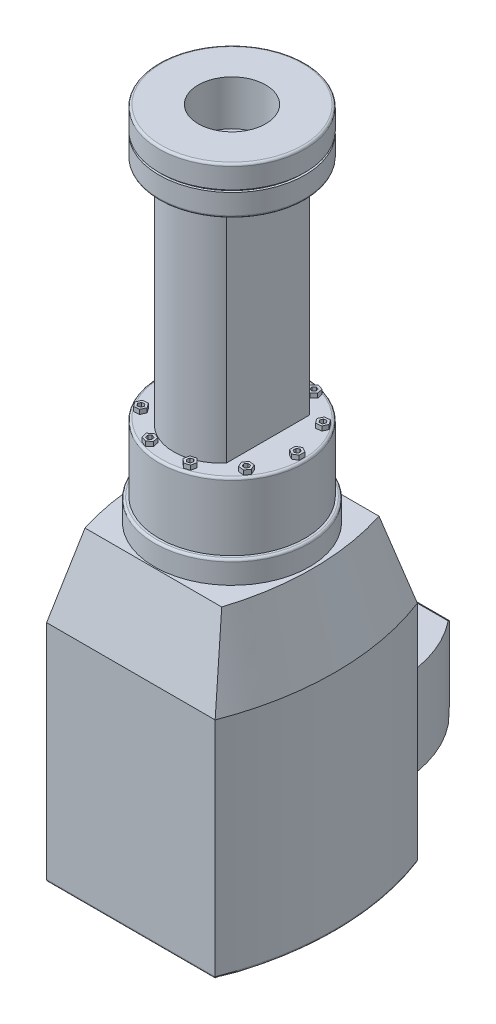
SolidWorks part; units mm, degrees
material "AISI 1020 Steel, Cold Rolled"
ref_plane "Front Plane" through (0, 0, 0) normal (0, 0, 1) x (1, 0, 0)
ref_plane "Top Plane" through (0, 0, 0) normal (0, 1, 0) x (1, 0, 0)
ref_plane "Right Plane" through (0, 0, 0) normal (1, 0, 0) x (0, 0, -1)
sketch "Sketch1" plane through (0, 0, 0) normal (0, 1, 0) x (1, 0, 0)
  line L0 (0, -45) -> (0, 45) construction
  line L1 (37.5, 45) -> (-37.5, 45)
  line L2 (37.5, -45) -> (-37.5, -45)
  arc A0 (-37.5, 45) -> (-37.5, -45) centre (79.119, 0) ccw
  arc A1 (37.5, 45) -> (37.5, -45) centre (-79.119, 0) cw
  point P4 (0, 0)
  point P7 (0, 45)
  point P11 (0, -45)
  dimension "D3" = 125
  dimension "D1" = 75
  dimension "D2" = 90
extrude "Boss-Extrude1" add sketch "Sketch1" along normal blind 100
sketch "Sketch2" plane through (0, 100, 0) normal (0, 1, 0) x (1, 0, 0)
  line L2 (-37.5, -45) -> (37.5, -45)
  line L3 (37.5, 45) -> (-37.5, 45)
  line L4 (-37.5, -45) -> (37.5, -45)
  line L5 (37.5, 45) -> (-37.5, 45)
  arc A2 (-37.5, 45) -> (-37.5, -45) centre (79.119, 0) ccw
  arc A3 (37.5, -45) -> (37.5, 45) centre (-79.119, 0) ccw
  arc A4 (-37.5, 45) -> (-37.5, -45) centre (79.119, 0) ccw
  arc A5 (37.5, -45) -> (37.5, 45) centre (-79.119, 0) ccw
  dimension "D1" = 0
ref_plane "Plane1" through (0, 135, 0) normal (0, 1, 0) x (1, 0, 0)
sketch "Sketch3" plane through (0, 135, 0) normal (0, 1, 0) x (1, 0, 0)
  line L5 (30.4255, 35) -> (-30.4255, 35)
  line L6 (-30.4255, -35) -> (30.4255, -35)
  line L7 (30.4255, 35) -> (-30.4255, 35)
  line L8 (-30.4255, -35) -> (30.4255, -35)
  arc A4 (-30.4255, 35) -> (-30.4255, -35) centre (79.119, 0) ccw
  arc A5 (30.4255, -35) -> (30.4255, 35) centre (-79.119, 0) ccw
  arc A6 (-30.4255, 35) -> (-30.4255, -35) centre (79.119, 0) ccw
  arc A7 (30.4255, -35) -> (30.4255, 35) centre (-79.119, 0) ccw
  dimension "D1" = 10
loft "Loft1" add profiles "Sketch2", "Sketch3"
sketch "Sketch4" plane through (0, 135, 0) normal (0, 1, 0) x (1, 0, 0)
  circle A0 centre (0, 0) radius 34.5
  dimension "D1" = 69
extrude "Boss-Extrude2" add sketch "Sketch4" along normal blind 10
sketch "Sketch5" plane through (0, 145, 0) normal (0, 1, 0) x (1, 0, 0)
  circle A2 centre (0, 0) radius 32.5
  circle A3 centre (0, 0) radius 32.5
  dimension "D1" = 2
extrude "Boss-Extrude3" add sketch "Sketch5" along normal blind 30
sketch "Sketch6" plane through (0, 175, 0) normal (0, 1, 0) x (1, 0, 0)
  line L0 (0, 0) -> (29, 0) construction
  line L1 (27.8349, -0.6726) -> (29, -1.3453)
  line L2 (29, 2.5) -> (26.8349, 1.25)
  line L3 (26.8349, 1.25) -> (26.8349, -1.25)
  line L4 (26.8349, -1.25) -> (29, -2.5)
  line L5 (29, -2.5) -> (31.1651, -1.25)
  line L6 (31.1651, -1.25) -> (31.1651, 1.25)
  line L7 (31.1651, 1.25) -> (29, 2.5)
  line L8 (29, -1.3453) -> (30.1651, -0.6726)
  line L9 (30.1651, -0.6726) -> (30.1651, 0.6726)
  line L10 (30.1651, 0.6726) -> (29, 1.3453)
  line L11 (29, 1.3453) -> (27.8349, 0.6726)
  line L12 (27.8349, 0.6726) -> (27.8349, -0.6726)
  circle A0 centre (29, 0) radius 2.1651 construction
  dimension "D1" = 29
  dimension "D2" = 5
  dimension "D3" = 1
extrude "Boss-Extrude4" add sketch "Sketch6" along normal blind 2
pattern_circular "CirPattern1" count 10 over 360 about axis through (0, 0, 0) along (0, 1, 0) of "Boss-Extrude4"
sketch "Sketch7" plane through (0, 175, 0) normal (0, 1, 0) x (1, 0, 0)
  line L0 (0, -14.804) -> (0, 14.804) construction
  line L1 (0, 0) -> (16, 0) construction
  line L2 (16, -18.5) -> (16, 18.5)
  line L3 (-16, -18.5) -> (-16, 18.5)
  arc A0 (-16, 18.5) -> (16, 18.5) centre (0, 4.8985) cw
  arc A1 (-16, -18.5) -> (16, -18.5) centre (0, -4.8985) ccw
  point P5 (0, 0)
  point P11 (16, 0)
  dimension "D3" = 21
  dimension "D1" = 16
  dimension "D2" = 37
extrude "Boss-Extrude5" add sketch "Sketch7" along normal blind 100
sketch "Sketch8" plane through (0, 275, 0) normal (0, 1, 0) x (1, 0, 0)
  circle A0 centre (0, 0) radius 32.5 construction
  circle A1 centre (0, 0) radius 32.5
extrude "Boss-Extrude6" add sketch "Sketch8" along normal blind 10
sketch "Sketch9" plane through (0, 285, 0) normal (0, 1, 0) x (1, 0, 0)
  circle A2 centre (0, 0) radius 31.5
  circle A3 centre (0, 0) radius 31.5
  dimension "D1" = 1
extrude "Boss-Extrude7" add sketch "Sketch9" along normal blind 1
sketch "Sketch10" plane through (0, 286, 0) normal (0, 1, 0) x (1, 0, 0)
  circle A0 centre (0, 0) radius 32.5 construction
  circle A1 centre (0, 0) radius 32.5
extrude "Boss-Extrude8" add sketch "Sketch10" along normal blind 10
ref_plane "Plane2" through (-37.5, 0, 0) normal (1, 0, 0) x (0, 0, -1)
sketch "Sketch11" plane through (-37.5, 0, 0) normal (1, 0, 0) x (0, 0, -1)
  line L0 (45, 100) -> (45, 0) construction
  circle A0 centre (45, 50) radius 42.5
  dimension "D1" = 85
extrude "Boss-Extrude9" add sketch "Sketch11" along normal mid plane 21
sketch "Sketch12" plane through (-27, 0, 0) normal (1, 0, 0) x (0, 0, -1)
  line L0 (45, 50) -> (75, 50) construction
  line L1 (45, 100) -> (45, 0) construction
  line L2 (45, 70) -> (75, 70)
  line L3 (45, 30) -> (75, 30)
  line L4 (45, 70) -> (45, 30)
  arc A0 (75, 70) -> (75, 30) centre (60.3189, 50) cw
  dimension "D3" = 24.81
  dimension "D1" = 30
  dimension "D2" = 20
extrude "Boss-Extrude10" add sketch "Sketch12" along normal blind 35
ref_plane "Plane3" through (0, 50, 0) normal (0, 1, 0) x (1, 0, 0)
sketch "Sketch13" plane through (0, 50, 0) normal (0, 1, 0) x (1, 0, 0)
  line L0 (33, 45) -> (8, 45)
  line L1 (37.5, 45) -> (-37.5, 45) construction
  line L2 (8, 45) -> (8, 87)
  arc A0 (8, 87) -> (33, 45) centre (-21.8393, 40.7981) cw
  dimension "D3" = 55
  dimension "D1" = 25
  dimension "D2" = 42
extrude "Boss-Extrude11" add sketch "Sketch13" along normal mid plane 40
sketch "Sketch14" plane through (8, 0, 0) normal (-1, 0, 0) x (0, 0, 1)
  line L3 (-87, 30) -> (-75, 30)
  line L4 (-75, 70) -> (-87, 70)
  line L5 (-87, 70) -> (-87, 30)
  line L6 (-87, 30) -> (-75, 30)
  line L7 (-75, 70) -> (-87, 70)
  line L8 (-87, 70) -> (-87, 30)
  arc A1 (-75, 70) -> (-75, 30) centre (-60.3189, 50) ccw
  arc A2 (-75, 70) -> (-75, 30) centre (-60.3189, 50) ccw
  dimension "D1" = 0
extrude "Cut-Extrude1" cut sketch "Sketch14" against normal through all
fillet "Fillet1" radius 1 8 edges at (0, 0, 45) (45.881, 0, 0) (0, 0, -45) (-45.881, 0, 0) (0, 145, 34.5) (0, 175, 32.5) (0, 296, 32.5) (0, 275, 32.5)
fillet "Fillet2" radius 1 2 edges at (-27, 50, -87.5) (-48, 50, -87.5)
sketch "Sketch15" plane through (0, 296, 0) normal (0, 1, 0) x (1, 0, 0)
  circle A0 centre (0, 0) radius 15
  dimension "D1" = 30
extrude "Cut-Extrude2" cut sketch "Sketch15" against normal blind 20
sketch "Sketch16" plane through (-48, 0, 0) normal (-1, 0, 0) x (0, 0, 1)
  circle A0 centre (-45, 50) radius 15
  dimension "D1" = 30
extrude "Cut-Extrude3" cut sketch "Sketch16" against normal blind 20
